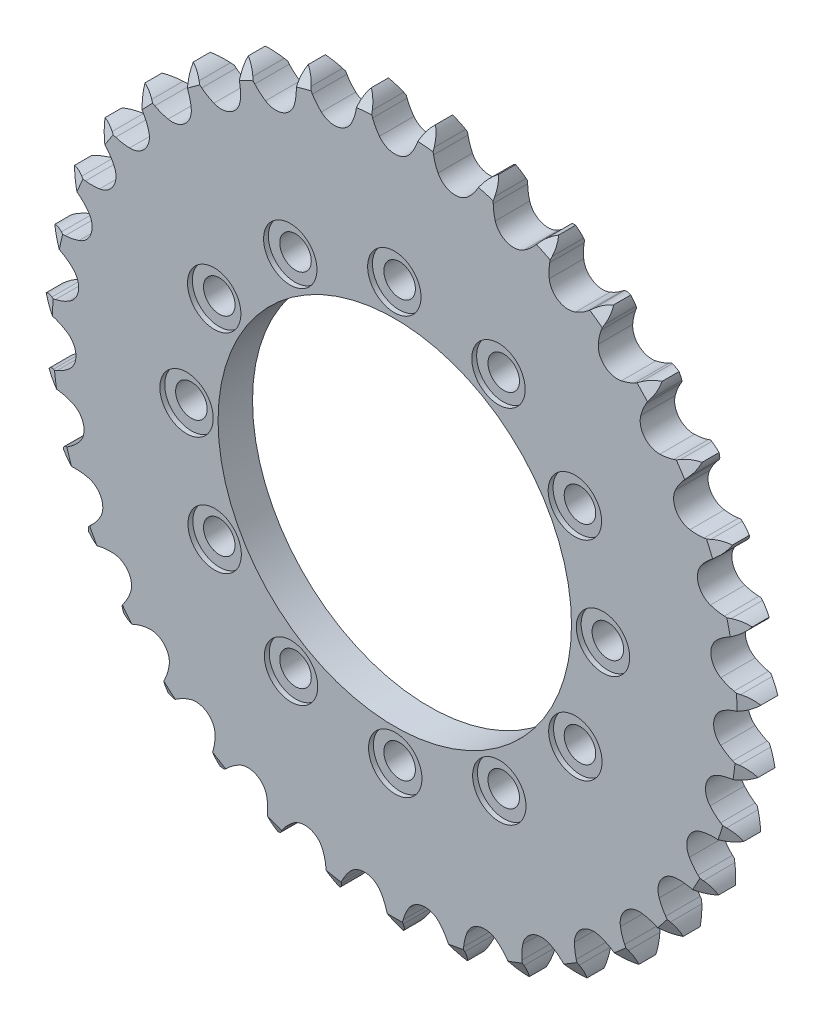
SolidWorks part; units mm, degrees
material "7075-T6 (SN)"
ref_plane "Front Plane" through (0, 0, 0) normal (0, 0, 1) x (1, 0, 0)
ref_plane "Top Plane" through (0, 0, 0) normal (0, 1, 0) x (1, 0, 0)
ref_plane "Right Plane" through (0, 0, 0) normal (1, 0, 0) x (0, 0, -1)
sketch "Work Sketch" plane through (0, 0, 0) normal (0, 0, 1) x (1, 0, 0)
  line L0 (0, 0) -> (0, 160.4542) construction
  line L1 (-112.0919, 70.8395) -> (87.2579, 70.8395) construction
  line L2 (5.0903, 120.8822) -> (5.0903, 112.9699) construction
  line L3 (-12.8497, 74.6356) -> (16.7256, 74.6356) construction
  line L4 (5.0903, 74.6356) -> (-6.074, 66.3097) construction
  line L5 (5.0903, 74.6356) -> (-4.641, 71.0332) construction
  line L6 (-4.641, 71.0332) -> (-6.9559, 77.2865)
  line L7 (-11.5114, 69.8433) -> (-7.1525, 69.8433) construction
  line L8 (-11.0678, 124.7602) -> (-11.0678, 110.2345) construction
  line L9 (0, 0) -> (-3.8324, 42.5811) construction
  circle A0 centre (0, 0) radius 70.8395
  circle A1 centre (0, 70.8395) radius 4.0088
  arc A2 (-4.641, 71.0332) -> (-3.2136, 68.4429) centre (5.0682, 74.6949) ccw
  circle A3 centre (-11.0678, 69.8433) radius 6.4401
  point P23 (-3.2136, 68.4429)
  dimension "D1" = 141.6789
  dimension "D8" = 10.3767
  dimension "D2" = 8.0177
  dimension "D3" = 5.0903
  dimension "D4" = 3.7962
  dimension "D5" = 36.714
  dimension "D6" = 16.4
  dimension "D7" = 10.3767
  dimension "D9" = 0.9961
  dimension "D10" = 11.0678
  dimension "D11" = 5.143
sketch "Teeth Sketch" plane through (0, 0, 0) normal (0, 0, 1) x (1, 0, 0)
  line L0 (5.0282, 72.0792) -> (4.641, 71.0332)
  line L1 (-8.3399, 92.6643) -> (-5.3292, 59.2127) construction
  line L2 (0, 0) -> (-12.1309, 132.2) construction
  line L3 (7.9229, 71.8186) -> (8.1171, 70.7203)
  line L4 (17927.8618, -199194.8588) -> (-17931.6941, 199237.4399) construction
  line L5 (0, 146.3285) -> (0, 56.9858) construction
  line L6 (17.8176, 70.023) -> (17.2498, 69.063)
  line L7 (0, -200000) -> (0, 200160.4542) construction
  line L8 (20.6192, 69.2498) -> (20.6142, 68.1345)
  line L9 (-4.641, 71.0332) -> (-6.9559, 77.2865) construction
  line L10 (43.6371, 57.589) -> (43.2405, 56.5465)
  line L11 (-5.0282, 72.0792) -> (-4.641, 71.0332)
  line L12 (30.0344, 65.7163) -> (29.3043, 64.873)
  line L13 (32.6529, 64.4552) -> (32.4488, 63.3587)
  line L14 (41.2858, 59.2973) -> (40.4169, 58.598)
  line L15 (51.2103, 50.9725) -> (50.2305, 50.4396)
  line L16 (53.2187, 48.8718) -> (52.6424, 47.9169)
  line L17 (59.4888, 41.0094) -> (58.4296, 40.66)
  line L18 (61.0899, 38.5838) -> (60.3523, 37.7472)
  line L19 (65.8553, 29.7283) -> (64.7507, 29.5736)
  line L20 (66.9976, 27.0558) -> (66.1224, 26.3643)
  line L21 (70.1052, 17.4916) -> (68.9907, 17.5366)
  line L22 (70.7519, 14.6581) -> (69.7673, 14.134)
  line L23 (72.1018, 4.6927) -> (71.0133, 4.9361)
  line L24 (72.2322, 1.7893) -> (71.1699, 1.4494)
  line L25 (71.781, -8.2569) -> (70.7534, -7.8232)
  line L26 (71.3909, -11.137) -> (70.2849, -11.2818)
  line L27 (69.1531, -20.9412) -> (68.2195, -20.331)
  line L28 (68.255, -23.7054) -> (67.141, -23.6503)
  line L29 (64.3026, -32.9525) -> (63.493, -32.1853)
  line L30 (62.9254, -35.5118) -> (61.8391, -35.2587)
  line L31 (57.3853, -43.9046) -> (56.7257, -43.0052)
  line L32 (55.5732, -46.1769) -> (54.5496, -45.7339)
  line L33 (48.6237, -53.4456) -> (48.1352, -52.4428)
  line L34 (46.435, -55.3578) -> (45.5069, -54.7392)
  line L35 (38.2992, -61.2688) -> (37.9976, -60.1949)
  line L36 (35.8042, -62.7594) -> (35.0015, -61.985)
  line L37 (26.7437, -67.1227) -> (26.6388, -66.0123)
  line L38 (24.0227, -68.144) -> (23.3712, -67.2387)
  line L39 (14.3287, -70.8193) -> (14.4237, -69.708)
  line L40 (11.4691, -71.3383) -> (10.9896, -70.3312)
  line L41 (1.4532, -72.2397) -> (1.7451, -71.1632)
  line L42 (-1.4532, -72.2397) -> (-1.7451, -71.1632)
  line L43 (-11.4691, -71.3383) -> (-10.9896, -70.3312)
  line L44 (-14.3287, -70.8193) -> (-14.4237, -69.708)
  line L45 (-24.0227, -68.144) -> (-23.3712, -67.2387)
  line L46 (-26.7437, -67.1227) -> (-26.6388, -66.0123)
  line L47 (-35.8042, -62.7594) -> (-35.0015, -61.985)
  line L48 (-38.2992, -61.2688) -> (-37.9976, -60.1949)
  line L49 (-46.435, -55.3578) -> (-45.5069, -54.7392)
  line L50 (-48.6237, -53.4456) -> (-48.1352, -52.4428)
  line L51 (-55.5732, -46.1769) -> (-54.5496, -45.7339)
  line L52 (-57.3853, -43.9046) -> (-56.7257, -43.0052)
  line L53 (-62.9254, -35.5118) -> (-61.8391, -35.2587)
  line L54 (-64.3026, -32.9525) -> (-63.493, -32.1853)
  line L55 (-68.255, -23.7054) -> (-67.141, -23.6503)
  line L56 (-69.1531, -20.9412) -> (-68.2195, -20.331)
  line L57 (-71.3909, -11.137) -> (-70.2849, -11.2818)
  line L58 (-71.781, -8.2569) -> (-70.7534, -7.8232)
  line L59 (-72.2322, 1.7893) -> (-71.1699, 1.4494)
  line L60 (-72.1018, 4.6927) -> (-71.0133, 4.9361)
  line L61 (-70.7519, 14.6581) -> (-69.7673, 14.134)
  line L62 (-70.1052, 17.4916) -> (-68.9907, 17.5366)
  line L63 (-66.9976, 27.0558) -> (-66.1224, 26.3643)
  line L64 (-65.8553, 29.7283) -> (-64.7507, 29.5736)
  line L65 (-61.0899, 38.5838) -> (-60.3523, 37.7472)
  line L66 (-59.4888, 41.0094) -> (-58.4296, 40.66)
  line L67 (-53.2187, 48.8718) -> (-52.6424, 47.9169)
  line L68 (-51.2103, 50.9725) -> (-50.2305, 50.4396)
  line L69 (-43.6371, 57.589) -> (-43.2405, 56.5465)
  line L70 (-41.2858, 59.2973) -> (-40.4169, 58.598)
  line L71 (-32.6529, 64.4552) -> (-32.4488, 63.3587)
  line L72 (-30.0344, 65.7163) -> (-29.3043, 64.873)
  line L73 (-20.6192, 69.2498) -> (-20.6142, 68.1345)
  line L74 (-17.8176, 70.023) -> (-17.2498, 69.063)
  line L75 (-7.9229, 71.8186) -> (-8.1171, 70.7203)
  arc A0 (-6.856, 74.7153) -> (-5.0282, 72.0792) centre (-11.0678, 69.8433) cw
  circle A1 centre (-11.0678, 69.8433) radius 6.4401 construction
  arc A2 (-3.2136, 68.4429) -> (-4.641, 71.0332) centre (5.0682, 74.6949) cw
  arc A3 (-4.641, 71.0332) -> (-3.2136, 68.4429) centre (5.0682, 74.6949) ccw construction
  circle A4 centre (0, 70.8395) radius 4.0088 construction
  arc A5 (-3.2136, 68.4429) -> (3.2136, 68.4429) centre (0, 70.8395) ccw
  arc A6 (3.2136, 68.4429) -> (4.641, 71.0332) centre (-5.0682, 74.6949) ccw
  arc A7 (6.856, 74.7153) -> (5.0282, 72.0792) centre (11.0678, 69.8433) ccw
  arc A8 (6.5951, 74.7388) -> (7.9229, 71.8186) centre (1.5811, 70.6972) cw
  arc A9 (9.059, 67.9168) -> (8.1171, 70.7203) centre (18.324, 72.5896) cw
  arc A10 (9.059, 67.9168) -> (15.3829, 66.7692) centre (12.6489, 69.701) ccw
  arc A11 (15.3829, 66.7692) -> (17.2498, 69.063) centre (8.3506, 74.3995) ccw
  arc A12 (20.0867, 72.2905) -> (17.8176, 70.023) centre (23.3609, 66.7447) ccw
  arc A13 (19.8343, 72.3601) -> (20.6192, 69.2498) centre (14.1792, 69.2787) cw
  arc A14 (21.0404, 65.2078) -> (20.6142, 68.1345) centre (30.9909, 68.1512) cw
  arc A15 (21.0404, 65.2078) -> (27.0578, 62.9494) centre (24.8912, 66.3224) ccw
  arc A16 (27.0578, 62.9494) -> (29.3043, 64.873) centre (21.5009, 71.7128) ccw
  arc A17 (32.6719, 67.5421) -> (30.0344, 65.7163) centre (34.9032, 61.5008) ccw
  arc A18 (32.4359, 67.6557) -> (32.6529, 64.4552) centre (26.3215, 65.6336) cw
  arc A19 (32.3456, 60.403) -> (32.4488, 63.3587) centre (42.6617, 61.5223) cw
  arc A20 (32.3456, 60.403) -> (37.863, 57.1065) centre (36.3335, 60.812) ccw
  arc A21 (37.863, 57.1065) -> (40.4169, 58.598) centre (33.9602, 66.7212) ccw
  arc A22 (44.207, 60.6229) -> (41.2858, 59.2973) centre (45.3237, 54.2803) ccw
  arc A23 (43.9951, 60.7768) -> (43.6371, 57.589) centre (37.6178, 59.8789) cw
  arc A24 (42.6112, 53.6567) -> (43.2405, 56.5465) centre (52.9614, 52.9161) cw
  arc A25 (42.6112, 53.6567) -> (47.4513, 49.428) centre (46.608, 53.3472) ccw
  arc A26 (47.4513, 49.428) -> (50.2305, 50.4396) centre (45.328, 59.5852) ccw
  arc A27 (54.3212, 51.7552) -> (51.2103, 50.9725) centre (54.2875, 45.3151) ccw
  arc A28 (54.1402, 51.9445) -> (53.2187, 48.8718) centre (47.7051, 52.1997) cw
  arc A29 (51.5072, 45.1859) -> (52.6424, 47.9169) centre (61.5588, 42.6091) cw
  arc A30 (51.5072, 45.1859) -> (55.5144, 40.161) centre (55.3845, 44.1677) ccw
  arc A31 (55.5144, 40.161) -> (58.4296, 40.66) centre (55.2389, 50.534) ccw
  arc A32 (62.6894, 41.224) -> (59.4888, 41.0094) centre (61.5064, 34.8935) ccw
  arc A33 (62.5452, 41.4426) -> (61.0899, 38.5838) centre (56.2591, 42.8428) cw
  arc A34 (58.7477, 35.2628) -> (60.3523, 37.7472) centre (68.1777, 30.9326) cw
  arc A35 (58.7477, 35.2628) -> (61.7933, 29.6031) centre (62.3809, 33.5686) ccw
  arc A36 (61.7933, 29.6031) -> (64.7507, 29.5736) centre (63.3744, 39.8586) ccw
  arc A37 (69.0428, 29.3679) -> (65.8553, 29.7283) centre (66.7484, 23.3503) ccw
  arc A38 (68.9399, 29.6087) -> (66.9976, 27.0558) centre (63.0048, 32.1088) cw
  arc A39 (64.1, 24.2063) -> (66.1224, 26.3643) centre (72.6052, 18.2619) cw
  arc A40 (64.1, 24.2063) -> (66.0861, 18.0937) centre (67.3723, 21.8906) ccw
  arc A41 (66.0861, 18.0937) -> (68.9907, 17.5366) centre (69.4729, 27.9021) ccw
  arc A42 (73.1771, 16.5679) -> (70.1052, 17.4916) centre (69.8451, 11.0567) ccw
  arc A43 (73.1188, 16.8232) -> (70.7519, 14.6581) centre (67.7256, 20.3429) cw
  arc A44 (67.3921, 12.3718) -> (69.7673, 14.134) centre (74.6992, 5.0042) cw
  arc A45 (67.3921, 12.3718) -> (68.2548, 6.0028) centre (70.1983, 9.509) ccw
  arc A46 (68.2548, 6.0028) -> (71.0133, 4.9361) centre (73.3386, 15.0489) ccw
  arc A47 (74.9595, 3.2354) -> (72.1018, 4.6927) centre (70.6969, -1.5923) ccw
  arc A48 (74.9477, 3.497) -> (72.2322, 1.7893) centre (70.2696, 7.9231) cw
  arc A49 (68.5181, 0.1397) -> (71.1699, 1.4494) centre (74.3923, -8.4143) cw
  arc A50 (68.5181, 0.1397) -> (68.2298, -6.281) centre (70.7681, -3.1782) ccw
  arc A51 (68.2298, -6.281) -> (70.7534, -7.8232) centre (74.8471, 1.7119) ccw
  arc A52 (74.3325, -10.2012) -> (71.781, -8.2569) centre (69.2765, -14.1901) ccw
  arc A53 (74.3677, -9.9416) -> (71.3909, -11.137) centre (70.555, -4.7513) cw
  arc A54 (67.442, -12.097) -> (70.2849, -11.2818) centre (71.6944, -21.5623) cw
  arc A55 (67.442, -12.097) -> (66.0118, -18.363) centre (69.0634, -15.7633) ccw
  arc A56 (66.0118, -18.363) -> (68.2195, -20.331) centre (73.9499, -11.6801) ccw
  arc A57 (71.3165, -23.3098) -> (69.1531, -20.9412) centre (65.6294, -26.3319) ccw
  arc A58 (71.3974, -23.0607) -> (68.255, -23.7054) centre (68.5728, -17.2731) cw
  arc A59 (64.1981, -23.9448) -> (67.141, -23.6503) centre (66.6921, -34.0173) cw
  arc A60 (64.1981, -23.9448) -> (61.6721, -29.8547) centre (65.1388, -27.8417) ccw
  arc A61 (61.6721, -29.8547) -> (63.493, -32.1853) centre (70.676, -24.6966) ccw
  arc A62 (66.0083, -35.6693) -> (64.3026, -32.9525) centre (59.873, -37.6273) ccw
  arc A63 (66.1324, -35.4386) -> (62.9254, -35.5118) centre (64.3866, -29.2396) cw
  arc A64 (58.8909, -35.023) -> (61.8391, -35.2587) centre (59.5463, -45.379) cw
  arc A65 (58.8909, -35.023) -> (55.3502, -40.3869) centre (59.1207, -39.0252) ccw
  arc A66 (55.3502, -40.3869) -> (56.7257, -43.0052) centre (65.1304, -36.9194) ccw
  arc A67 (58.5785, -46.8823) -> (57.3853, -43.9046) centre (52.1922, -47.7133) ccw
  arc A68 (58.7418, -46.6775) -> (55.5732, -46.1769) centre (58.1309, -40.2664) cw
  arc A69 (51.6909, -44.9755) -> (54.5496, -45.7339) centre (50.4867, -55.2821) cw
  arc A70 (51.6909, -44.9755) -> (47.2494, -49.6211) centre (51.2024, -48.9545) ccw
  arc A71 (47.2494, -49.6211) -> (48.1352, -52.4428) centre (57.4915, -47.9556) ccw
  arc A72 (49.266, -56.5885) -> (48.6237, -53.4456) centre (42.8339, -56.2658) ccw
  arc A73 (49.4632, -56.4161) -> (46.435, -55.3578) centre (50.0069, -49.999) cw
  arc A74 (42.8296, -53.4825) -> (45.5069, -54.7392) centre (39.8043, -63.4085) cw
  arc A75 (42.8296, -53.4825) -> (37.6299, -57.2603) centre (41.6384, -57.3103) ccw
  arc A76 (37.6299, -57.2603) -> (37.9976, -60.1949) centre (48.0048, -57.4505) ccw
  arc A77 (38.37, -64.4758) -> (38.2992, -61.2688) centre (32.0989, -63.0099) ccw
  arc A78 (38.5948, -64.3415) -> (35.8042, -62.7594) centre (40.2756, -58.1246) cw
  arc A79 (32.5916, -60.2706) -> (35.0015, -61.985) centre (27.8426, -69.4968) cw
  arc A80 (32.5916, -60.2706) -> (26.8009, -63.0592) centre (30.7361, -63.8241) ccw
  arc A81 (26.8009, -63.0592) -> (26.6388, -66.0123) centre (36.9752, -65.0988) ccw
  arc A82 (26.2407, -70.2909) -> (26.7437, -67.1227) centre (20.3322, -67.7288) ccw
  arc A83 (26.4859, -70.1989) -> (24.0227, -68.144) centre (29.2498, -64.382) cw
  arc A84 (21.3061, -65.1215) -> (23.3712, -67.2387) centre (14.9861, -73.3515) cw
  arc A85 (21.3061, -65.1215) -> (15.1105, -66.8313) centre (18.8459, -68.2866) ccw
  arc A86 (15.1105, -66.8313) -> (14.4237, -69.708) centre (24.7571, -70.6548) ccw
  arc A87 (13.2681, -73.8468) -> (14.3287, -70.8193) centre (7.912, -70.2708) ccw
  arc A88 (13.5258, -73.8) -> (11.4691, -71.3383) centre (17.2839, -68.5701) cw
  arc A89 (9.3358, -67.8793) -> (10.9896, -70.3312) centre (1.6478, -74.8485) cw
  arc A90 (9.3358, -67.8793) -> (2.9345, -68.4554) centre (6.35, -70.5543) ccw
  arc A91 (2.9345, -68.4554) -> (1.7451, -71.1632) centre (11.7434, -73.9399) ccw
  arc A92 (-0.131, -75.0291) -> (1.4532, -72.2397) centre (-4.7625, -70.5543) ccw
  arc A93 (0.131, -75.0291) -> (-1.4532, -72.2397) centre (4.7625, -70.5543) cw
  arc A94 (-2.9345, -68.4554) -> (-1.7451, -71.1632) centre (-11.7434, -73.9399) cw
  arc A95 (-2.9345, -68.4554) -> (-9.3358, -67.8793) centre (-6.35, -70.5543) ccw
  arc A96 (-9.3358, -67.8793) -> (-10.9896, -70.3312) centre (-1.6478, -74.8485) ccw
  arc A97 (-13.5258, -73.8) -> (-11.4691, -71.3383) centre (-17.2839, -68.5701) ccw
  arc A98 (-13.2681, -73.8468) -> (-14.3287, -70.8193) centre (-7.912, -70.2708) cw
  arc A99 (-15.1105, -66.8313) -> (-14.4237, -69.708) centre (-24.7571, -70.6548) cw
  arc A100 (-15.1105, -66.8313) -> (-21.3061, -65.1215) centre (-18.8459, -68.2866) ccw
  arc A101 (-21.3061, -65.1215) -> (-23.3712, -67.2387) centre (-14.9861, -73.3515) ccw
  arc A102 (-26.4859, -70.1989) -> (-24.0227, -68.144) centre (-29.2498, -64.382) ccw
  arc A103 (-26.2407, -70.2909) -> (-26.7437, -67.1227) centre (-20.3322, -67.7288) cw
  arc A104 (-26.8009, -63.0592) -> (-26.6388, -66.0123) centre (-36.9752, -65.0988) cw
  arc A105 (-26.8009, -63.0592) -> (-32.5916, -60.2706) centre (-30.7361, -63.8241) ccw
  arc A106 (-32.5916, -60.2706) -> (-35.0015, -61.985) centre (-27.8426, -69.4968) ccw
  arc A107 (-38.5948, -64.3415) -> (-35.8042, -62.7594) centre (-40.2756, -58.1246) ccw
  arc A108 (-38.37, -64.4758) -> (-38.2992, -61.2688) centre (-32.0989, -63.0099) cw
  arc A109 (-37.6299, -57.2603) -> (-37.9976, -60.1949) centre (-48.0048, -57.4505) cw
  arc A110 (-37.6299, -57.2603) -> (-42.8296, -53.4825) centre (-41.6384, -57.3103) ccw
  arc A111 (-42.8296, -53.4825) -> (-45.5069, -54.7392) centre (-39.8043, -63.4085) ccw
  arc A112 (-49.4632, -56.4161) -> (-46.435, -55.3578) centre (-50.0069, -49.999) ccw
  arc A113 (-49.266, -56.5885) -> (-48.6237, -53.4456) centre (-42.8339, -56.2658) cw
  arc A114 (-47.2494, -49.6211) -> (-48.1352, -52.4428) centre (-57.4915, -47.9556) cw
  arc A115 (-47.2494, -49.6211) -> (-51.6909, -44.9755) centre (-51.2024, -48.9545) ccw
  arc A116 (-51.6909, -44.9755) -> (-54.5496, -45.7339) centre (-50.4867, -55.2821) ccw
  arc A117 (-58.7418, -46.6775) -> (-55.5732, -46.1769) centre (-58.1309, -40.2664) ccw
  arc A118 (-58.5785, -46.8823) -> (-57.3853, -43.9046) centre (-52.1922, -47.7133) cw
  arc A119 (-55.3502, -40.3869) -> (-56.7257, -43.0052) centre (-65.1304, -36.9194) cw
  arc A120 (-55.3502, -40.3869) -> (-58.8909, -35.023) centre (-59.1207, -39.0252) ccw
  arc A121 (-58.8909, -35.023) -> (-61.8391, -35.2587) centre (-59.5463, -45.379) ccw
  arc A122 (-66.1324, -35.4386) -> (-62.9254, -35.5118) centre (-64.3866, -29.2396) ccw
  arc A123 (-66.0083, -35.6693) -> (-64.3026, -32.9525) centre (-59.873, -37.6273) cw
  arc A124 (-61.6721, -29.8547) -> (-63.493, -32.1853) centre (-70.676, -24.6966) cw
  arc A125 (-61.6721, -29.8547) -> (-64.1981, -23.9448) centre (-65.1388, -27.8417) ccw
  arc A126 (-64.1981, -23.9448) -> (-67.141, -23.6503) centre (-66.6921, -34.0173) ccw
  arc A127 (-71.3974, -23.0607) -> (-68.255, -23.7054) centre (-68.5728, -17.2731) ccw
  arc A128 (-71.3165, -23.3098) -> (-69.1531, -20.9412) centre (-65.6294, -26.3319) cw
  arc A129 (-66.0118, -18.363) -> (-68.2195, -20.331) centre (-73.9499, -11.6801) cw
  arc A130 (-66.0118, -18.363) -> (-67.442, -12.097) centre (-69.0634, -15.7633) ccw
  arc A131 (-67.442, -12.097) -> (-70.2849, -11.2818) centre (-71.6944, -21.5623) ccw
  arc A132 (-74.3677, -9.9416) -> (-71.3909, -11.137) centre (-70.555, -4.7513) ccw
  arc A133 (-74.3325, -10.2012) -> (-71.781, -8.2569) centre (-69.2765, -14.1901) cw
  arc A134 (-68.2298, -6.281) -> (-70.7534, -7.8232) centre (-74.8471, 1.7119) cw
  arc A135 (-68.2298, -6.281) -> (-68.5181, 0.1397) centre (-70.7681, -3.1782) ccw
  arc A136 (-68.5181, 0.1397) -> (-71.1699, 1.4494) centre (-74.3923, -8.4143) ccw
  arc A137 (-74.9477, 3.497) -> (-72.2322, 1.7893) centre (-70.2696, 7.9231) ccw
  arc A138 (-74.9595, 3.2354) -> (-72.1018, 4.6927) centre (-70.6969, -1.5923) cw
  arc A139 (-68.2548, 6.0028) -> (-71.0133, 4.9361) centre (-73.3386, 15.0489) cw
  arc A140 (-68.2548, 6.0028) -> (-67.3921, 12.3718) centre (-70.1983, 9.509) ccw
  arc A141 (-67.3921, 12.3718) -> (-69.7673, 14.134) centre (-74.6992, 5.0042) ccw
  arc A142 (-73.1188, 16.8232) -> (-70.7519, 14.6581) centre (-67.7256, 20.3429) ccw
  arc A143 (-73.1771, 16.5679) -> (-70.1052, 17.4916) centre (-69.8451, 11.0567) cw
  arc A144 (-66.0861, 18.0937) -> (-68.9907, 17.5366) centre (-69.4729, 27.9021) cw
  arc A145 (-66.0861, 18.0937) -> (-64.1, 24.2063) centre (-67.3723, 21.8906) ccw
  arc A146 (-64.1, 24.2063) -> (-66.1224, 26.3643) centre (-72.6052, 18.2619) ccw
  arc A147 (-68.9399, 29.6087) -> (-66.9976, 27.0558) centre (-63.0048, 32.1088) ccw
  arc A148 (-69.0428, 29.3679) -> (-65.8553, 29.7283) centre (-66.7484, 23.3503) cw
  arc A149 (-61.7933, 29.6031) -> (-64.7507, 29.5736) centre (-63.3744, 39.8586) cw
  arc A150 (-61.7933, 29.6031) -> (-58.7477, 35.2628) centre (-62.3809, 33.5686) ccw
  arc A151 (-58.7477, 35.2628) -> (-60.3523, 37.7472) centre (-68.1777, 30.9326) ccw
  arc A152 (-62.5452, 41.4426) -> (-61.0899, 38.5838) centre (-56.2591, 42.8428) ccw
  arc A153 (-62.6894, 41.224) -> (-59.4888, 41.0094) centre (-61.5064, 34.8935) cw
  arc A154 (-55.5144, 40.161) -> (-58.4296, 40.66) centre (-55.2389, 50.534) cw
  arc A155 (-55.5144, 40.161) -> (-51.5072, 45.1859) centre (-55.3845, 44.1677) ccw
  arc A156 (-51.5072, 45.1859) -> (-52.6424, 47.9169) centre (-61.5588, 42.6091) ccw
  arc A157 (-54.1402, 51.9445) -> (-53.2187, 48.8718) centre (-47.7051, 52.1997) ccw
  arc A158 (-54.3212, 51.7552) -> (-51.2103, 50.9725) centre (-54.2875, 45.3151) cw
  arc A159 (-47.4513, 49.428) -> (-50.2305, 50.4396) centre (-45.328, 59.5852) cw
  arc A160 (-47.4513, 49.428) -> (-42.6112, 53.6567) centre (-46.608, 53.3472) ccw
  arc A161 (-42.6112, 53.6567) -> (-43.2405, 56.5465) centre (-52.9614, 52.9161) ccw
  arc A162 (-43.9951, 60.7768) -> (-43.6371, 57.589) centre (-37.6178, 59.8789) ccw
  arc A163 (-44.207, 60.6229) -> (-41.2858, 59.2973) centre (-45.3237, 54.2803) cw
  arc A164 (-37.863, 57.1065) -> (-40.4169, 58.598) centre (-33.9602, 66.7212) cw
  arc A165 (-37.863, 57.1065) -> (-32.3456, 60.403) centre (-36.3335, 60.812) ccw
  arc A166 (-32.3456, 60.403) -> (-32.4488, 63.3587) centre (-42.6617, 61.5223) ccw
  arc A167 (-32.4359, 67.6557) -> (-32.6529, 64.4552) centre (-26.3215, 65.6336) ccw
  arc A168 (-32.6719, 67.5421) -> (-30.0344, 65.7163) centre (-34.9032, 61.5008) cw
  arc A169 (-27.0578, 62.9494) -> (-29.3043, 64.873) centre (-21.5009, 71.7128) cw
  arc A170 (-27.0578, 62.9494) -> (-21.0404, 65.2078) centre (-24.8912, 66.3224) ccw
  arc A171 (-21.0404, 65.2078) -> (-20.6142, 68.1345) centre (-30.9909, 68.1512) ccw
  arc A172 (-19.8343, 72.3601) -> (-20.6192, 69.2498) centre (-14.1792, 69.2787) ccw
  arc A173 (-20.0867, 72.2905) -> (-17.8176, 70.023) centre (-23.3609, 66.7447) cw
  arc A174 (-15.3829, 66.7692) -> (-17.2498, 69.063) centre (-8.3506, 74.3995) cw
  arc A175 (-15.3829, 66.7692) -> (-9.059, 67.9168) centre (-12.6489, 69.701) ccw
  arc A176 (-9.059, 67.9168) -> (-8.1171, 70.7203) centre (-18.324, 72.5896) ccw
  arc A177 (-6.5951, 74.7388) -> (-7.9229, 71.8186) centre (-1.5811, 70.6972) ccw
  point P77 (0, 0)
  dimension "D1" = 5.143
  dimension "D2" = 5.243
  dimension "D3" = 35
extrude "Extrusion" add sketch "Teeth Sketch" along normal blind 7.2136
hole_wizard "M6 Clearance Hole1" positions "Sketch6" profile "Sketch7" hole size "M6" standard "ANSI Metric"
sketch "Sketch6" plane through (0, 0, 0) normal (0, 0, -1) x (-1, 0, 0)
  circle A0 centre (0, 0) radius 43.5
  point P0 (0, 43.5)
  dimension "D1" = 87
sketch "Sketch7" plane through (0, 43.5, 0) normal (1, 0, 0) x (0, 1, 0)
  line L0 (0, 0) -> (0, 19.2548)
  line L1 (0, 19.2548) -> (3.3, 17.272)
  line L2 (3.3, 17.272) -> (3.3, 0)
  line L5 (3.3, 0) -> (0, 0)
  line L10 (0, 19.2548) -> (-3.3, 17.272) construction
  line L11 (0, -6.35) -> (0, 107.95) construction
  dimension "Hole Dia." = 6.6
  dimension "Hole Depth" = 17.272
  dimension "Drill Angle" = 118
pattern_circular "CirPattern1" count 12 over 360 about axis through (0, -0.0982, 0) along (0, 0, 1) of "M6 Clearance Hole1"
sketch "Sketch8" plane through (0, 0, 0) normal (0, 0, -1) x (-1, 0, 0)
  circle A0 centre (0, 0) radius 37
  dimension "D1" = 74
extrude "Cut-Extrude1" cut sketch "Sketch8" against normal through all both and the other way through all
ref_plane "Sprocket Center Plane" through (0, 0, 3.6068) normal (0, 0, 1) x (1, 0, 0)
sketch "Pitch Circle" plane through (0, 0, 3.6068) normal (0, 0, -1) x (-1, 0, 0)
  circle A0 centre (0, 0) radius 70.8395 construction
  dimension "D1" = 141.6789
ref_plane "Center Plane" through (0, 0, 3.6068) normal (0, 0, 1) x (1, 0, 0)
ref_axis "Axis1" through (0, 0, 7.2136) along (0, 0, -1)
sketch "Sketch5" plane through (0, 0, 0) normal (1, 0, 0) x (0, 0, -1)
  line L0 (-1.8288, -74.8895) -> (-5.3848, -74.8895)
  line L1 (-7.2136, -64.2888) -> (0, -64.2888) construction
  line L2 (-5.3848, -74.8895) -> (-5.3848, -71.6959)
  line L3 (-5.3848, -71.6959) -> (-7.2136, -71.6959)
  line L4 (-7.2136, -71.6959) -> (-5.3848, -74.8895)
  line L5 (-7.2136, -71.6959) -> (-7.2136, -74.8895)
  line L6 (-7.2136, -74.8895) -> (-5.3848, -74.8895)
  line L7 (-7.2136, -74.8895) -> (0, -74.8895) construction
  dimension "D1" = 3.556
  dimension "D2" = 3.1936
  dimension "D3" = 1.8288
revolve "Cut-Revolve1" cut sketch "Sketch5" angle 360 about axis through (0, 0, 7.2136) along (0, 0, -1)
mirror "Mirror1" about plane through (0, 0, 3.6068) normal (0, 0, 1) of "Cut-Revolve1"
sketch "Sketch10" plane through (0, 0, 0) normal (0, 0, 1) x (1, 0, 0)
  circle A0 centre (-43.5982, -0.0982) radius 5.588
  dimension "D1" = 11.176
extrude "Cut-Extrude2" cut sketch "Sketch10" against normal blind 1.016 from surface at 7.2136 starting at face at (-37, 0, 7.2136)
pattern_circular "CirPattern2" count 12 over 360 about axis through (0, 0, 0) along (0, 0, 1) of "Cut-Extrude2"
ref_plane "Half Plane" through (0, 0, 3.6068) normal (0, 0, 1) x (1, 0, 0)
sketch "Motor Shaft Sprocket Dimensions" plane through (0, 0, 3.6068) normal (0, 0, 1) x (1, 0, 0)
  line L0 (0, 0) -> (-177.8, 0)
  line L1 (-177.8, 0) -> (-177.8, 23.6982)
  line L2 (-180.8603, 51.0356) -> (-7.8809, 70.3997)
  line L3 (-187.9136, -1.8834) -> (-26.0447, -65.8779)
  line L4 (-7.8809, 70.3997) -> (0, 0)
  line L5 (0, 0) -> (-26.0447, -65.8779)
  circle A0 centre (-177.8, 23.6982) radius 27.5082
  circle A1 centre (0, 0) radius 70.8395 construction
  dimension "D3" = 55.0164
  dimension "D1" = 177.8
  dimension "D2" = 23.6982
  dimension "D4" = 207.959
equation "\"P\"= 0.500'//Chain Pitch"
equation "\"N\"= 35'//Number of Teeth"
equation "\"Dr\"= 5 / 16'//Roller Diameter"
equation "\"Ds\"= 1.0005 * \"Dr\" + 0.003'Seating Curve DIameter"
equation "\"R\"= \"Ds\" / 2"
equation "\"A\"= 35 + 60 / \"N\""
equation "\"B\"= 18 - 56 / \"N\""
equation "\"ac\"= 0.8 * \"Dr\""
equation "\"M\"= 0.8 * \"Dr\" * cos ( 35 + 60 / \"N\" )"
equation "\"T\"= 0.8 * \"Dr\" * sin ( 35 + 60 / \"N\" )"
equation "\"E\"= 1.3025 * \"Dr\" + 0.0015"
equation "\"Chordal Length of Arc xy\"= ( 2.605 * \"Dr\" + 0.003 ) * sin ( 9 - 28 / \"N\" )"
equation "\"yz\"= \"Dr\" * ( 1.4 * sin ( 17 - 64 / \"N\" ) - 0.8 * sin ( 18 - 56 / \"N\" ) )"
equation "\"ab\"= 1.4 * \"Dr\""
equation "\"W\"= 1.4 * \"Dr\" * cos ( 180 / \"N\" )"
equation "\"V\"= 1.4 * \"Dr\" * sin ( 180 / \"N\" )"
equation "\"F\"= \"Dr\" * ( 0.8 * cos ( 18 - 56 / \"N\" ) + 1.4 * cos ( 17 - 64 / \"N\" ) - 1.3025 )"
equation "\"H\"= sqr ( \"F\" ^ 2 - ( 1.4 * \"Dr\" - \"P\" / 2 ) ^ 2 )"
equation "\"S\"= \"P\" / 2 * cos ( 180 / \"N\" ) + \"H\" * sin ( 180 / \"N\" )"
equation "\"PD\"= \"P\" / ( sin ( 180 / \"N\" ) )"
equation "\"D1@Work Sketch\" = \"PD\""
equation "\"D3@Work Sketch\" = \"M\""
equation "\"D4@Work Sketch\" = \"T\""
equation "\"D5@Work Sketch\" = \"A\""
equation "\"D6@Work Sketch\" = \"B\""
equation "\"D7@Work Sketch\" = \"E\""
equation "\"D8@Work Sketch\" = \"E\""
equation "\"D9@Work Sketch\" = \"V\""
equation "\"D10@Work Sketch\" = \"W\""
equation "\"D2@Work Sketch\" = \"R\" * 2"
equation "\"D11@Work Sketch\" = 180 / \"N\""
equation "\"D2@Teeth Sketch\" = 180 / \"N\" + 0.1"
equation "\"D3@Teeth Sketch\" = \"N\""
equation "\"Edge Thickness\"=0.5"
equation "\"D1@Pitch Circle\"=\"PD\""
equation "\"ST\"= 0.284'//Sprocket Thickness"
